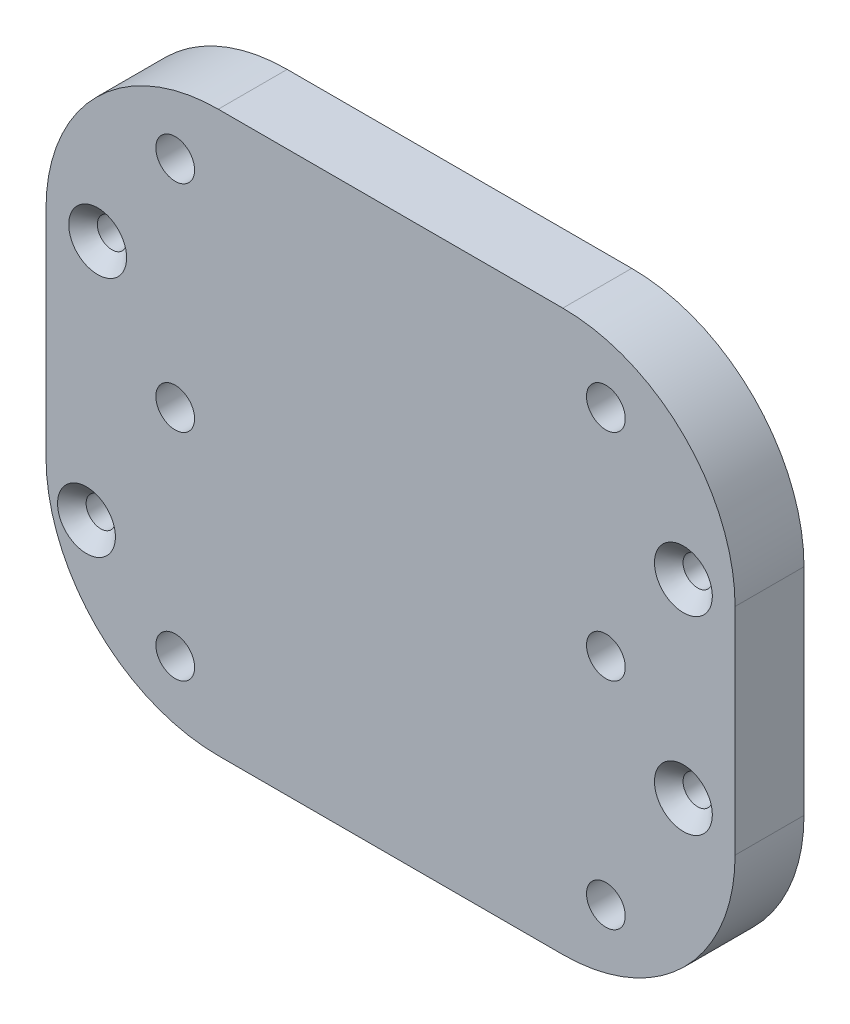
SolidWorks part; units mm, degrees
material "6061-T6 (SS)"
ref_plane "Front Plane" through (0, 0, 0) normal (0, 0, 1) x (1, 0, 0)
ref_plane "Top Plane" through (0, 0, 0) normal (0, 1, 0) x (1, 0, 0)
ref_plane "Right Plane" through (0, 0, 0) normal (1, 0, 0) x (0, 0, -1)
sketch "Sketch1" plane through (0, 0, 0) normal (0, 0, 1) x (1, 0, 0)
  line L0 (0, 0) -> (0, 65)
  line L1 (0, 65) -> (85, 65)
  line L2 (85, 65) -> (85, 0)
  line L3 (85, 0) -> (0, 0)
  dimension "D1" = 65
  dimension "D2" = 85
extrude "Boss-Extrude1" add sketch "Sketch1" along normal blind 8
sketch "Sketch2" plane through (0, 0, 8) normal (0, 0, 1) x (1, 0, 0)
  line L0 (0, 30.5535) -> (85, 30.5535) construction
  line L1 (0, 65) -> (0, 0) construction
  line L2 (85, 0) -> (85, 65) construction
  line L3 (42.5, 65) -> (42.5, 0) construction
  line L4 (85, 65) -> (0, 65) construction
  line L5 (0, 0) -> (85, 0) construction
  line L6 (4.2, -72.5717) -> (4, 53.2283) construction
  line L7 (4, 53.2283) -> (82.9172, 53.0283) construction
  line L8 (82.9172, 53.0283) -> (85.8, 50.1455)
  line L9 (85.8, 50.1455) -> (85.8, -72.5717) construction
  line L10 (85.8, -72.5717) -> (4.2, -72.5717) construction
  line L11 (-72.7002, -79.7833) -> (-72.7002, -89.7833)
  line L12 (-72.7002, -89.7833) -> (-38.7002, -89.7833)
  line L13 (-38.7002, -89.7833) -> (-38.7002, -79.7833)
  circle A0 centre (11, -54.2717) radius 1.25 construction
  circle A1 centre (9.7, 16.0283) radius 1.25
  circle A2 centre (11, 44.7283) radius 1.25
  circle A4 centre (45, 16.2283) radius 2.25
  circle A7 centre (79, 49.2283) radius 1.25
  circle A8 centre (79, 44.7283) radius 1.25
  circle A9 centre (79, 22.7283) radius 1.25
  circle A10 centre (79, -27.2717) radius 1.25 construction
  circle A11 centre (79, -54.2717) radius 1.25 construction
  circle A12 centre (45, -53.7717) radius 2.25 construction
  circle A13 centre (51.5, -53.7717) radius 1.25 construction
  circle A14 centre (53.5, -27.2717) radius 1.25 construction
  circle A15 centre (11, -63.2717) radius 1.25 construction
  circle A16 centre (7, -63.7717) radius 2.75 construction
sketch "Sketch3" plane through (0, 0, 0) normal (0, 0, -1) x (-1, 0, 0)
  line L0 (-85, 0) -> (-85, 65) construction
  line L2 (-70, 32.5) -> (-20, 32.5) construction
  line L3 (-20, 7.5) -> (-70, 7.5) construction
  line L4 (-85, 65) -> (0, 65) construction
  line L5 (-42.5, 65) -> (-42.5, 0) construction
  line L6 (-70, 0) -> (-70, 65) construction
  line L7 (0, 0) -> (-85, 0) construction
  line L8 (-20, 0) -> (-20, 65) construction
  circle A0 centre (-70, 57.5) radius 2
  circle A1 centre (-20, 57.5) radius 2
  circle A2 centre (-70, 32.5) radius 2
  circle A3 centre (-20, 32.5) radius 2
  circle A4 centre (-70, 7.5) radius 2
  circle A5 centre (-20, 7.5) radius 2
  dimension "D4" = 4
  dimension "D5" = 4
  dimension "D6" = 4
  dimension "D7" = 4
  dimension "D8" = 4
  dimension "D9" = 4
  dimension "D2" = 15
  dimension "D3" = 25
  dimension "D12" = 50
hole_wizard "CSK for M4 Hex Socket Countersunk Cap Screw1" positions "Sketch4" profile "Sketch5" countersink size "M4" standard "ISO"
sketch "Sketch4" plane through (0, 0, 0) normal (0, 0, -1) x (-1, 0, 0)
  point P0 (-70, 57.5)
  point P3 (-20, 57.5)
  point P6 (-20, 32.5)
  point P9 (-70, 32.5)
  point P12 (-70, 7.5)
  point P15 (-20, 7.5)
sketch "Sketch5" plane through (70, 57.5, 0) normal (1, 0, 0) x (0, 1, 0)
  line L0 (0, 0) -> (0, 12)
  line L1 (0, 12) -> (2.25, 10.6481)
  line L2 (2.25, 10.6481) -> (2.25, 2.23)
  line L3 (2.25, 2.23) -> (4.48, 0)
  line L5 (4.48, 0) -> (0, 0)
  line L6 (-2.25, 2.23) -> (-4.48, 0) construction
  line L10 (0, 12) -> (-2.25, 10.6481) construction
  line L11 (0, -6.35) -> (0, 107.95) construction
  dimension "Hole Dia." = 4.5
  dimension "Hole Depth" = 12
  dimension "Near C'Sink Dia." = 8.96
  dimension "Near C'Sink Angle" = 90
  dimension "Drill Angle" = 118
hole_wizard "CSK for M3 Hex Socket Countersunk Cap Screw1" positions "Sketch8" profile "Sketch9" countersink size "M3" standard "ISO"
sketch "Sketch8" plane through (0, 0, 8) normal (0, 0, 1) x (1, 0, 0)
  point P0 (11, 44.7283)
  point P9 (79, 44.7283)
  point P12 (79, 22.7283)
  point P18 (9.7, 16.0283)
sketch "Sketch9" plane through (11, 44.7283, 8) normal (1, 0, 0) x (0, -1, 0)
  line L0 (0, 0) -> (0, 12)
  line L1 (0, 12) -> (1.7, 10.9785)
  line L2 (1.7, 10.9785) -> (1.7, 1.66)
  line L3 (1.7, 1.66) -> (3.36, 0)
  line L5 (3.36, 0) -> (0, 0)
  line L6 (-1.7, 1.66) -> (-3.36, 0) construction
  line L10 (0, 12) -> (-1.7, 10.9785) construction
  line L11 (0, -6.35) -> (0, 107.95) construction
  dimension "Hole Dia." = 3.4
  dimension "Hole Depth" = 12
  dimension "Near C'Sink Dia." = 6.72
  dimension "Near C'Sink Angle" = 90
  dimension "Drill Angle" = 118
sketch "Sketch11" plane through (0, 0, 8) normal (0, 0, 1) x (1, 0, 0)
  line L1 (0, 65) -> (5, 65)
  line L2 (0, 65) -> (0, 0)
  line L3 (0, 0) -> (5, 0)
  line L4 (0, 0) -> (85, 0)
  line L5 (85, 0) -> (85, 65)
  line L6 (85, 65) -> (0, 65)
  line L7 (0, 65) -> (0, 0)
  line L8 (0, 0) -> (85, 0)
  line L9 (85, 0) -> (85, 65)
  line L10 (85, 65) -> (0, 65)
  line L11 (0, 65) -> (0, 0)
  line L12 (5, 65) -> (5, 0)
  line L13 (0, 65) -> (5, 0) construction
  line L14 (0, 0) -> (5, 65) construction
  point P6 (2.5, 32.5)
  line M17 (0, 0) -> (85, 0)
  line M19 (85, 65) -> (0, 65)
  line M20 (0, 65) -> (0, 0)
  dimension "D2" = 5
  dimension "D1" = 0
extrude "Cut-Extrude1" cut sketch "Sketch11" against normal through all contours L12 M19 M20 M17
fillet "Fillet1" radius 20 4 edges at (5, 0, 4) (85, 0, 4) (85, 65, 4) (5, 65, 4)
